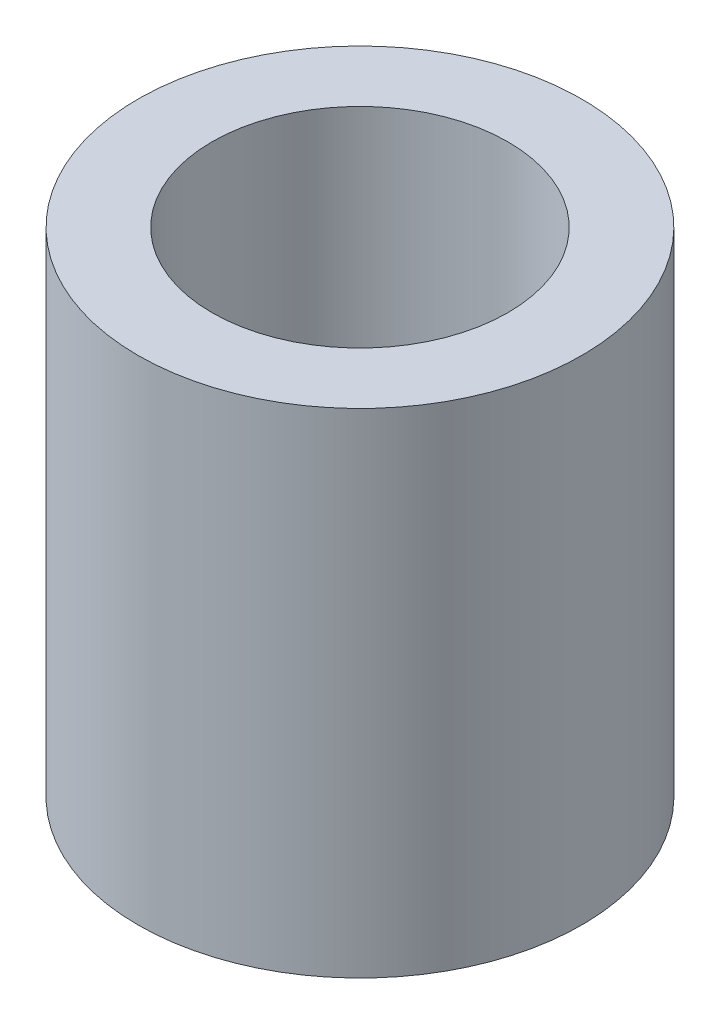
SolidWorks part; units mm, degrees
ref_plane "Front Plane" through (0, 0, 0) normal (0, 0, 1) x (1, 0, 0)
ref_plane "Top Plane" through (0, 0, 0) normal (0, 1, 0) x (1, 0, 0)
ref_plane "Right Plane" through (0, 0, 0) normal (1, 0, 0) x (0, 0, -1)
sketch "Sketch1" plane through (0, 0, 0) normal (0, 1, 0) x (1, 0, 0)
  circle A0 centre (0, 0) radius 1.5
  circle A1 centre (0, 0) radius 2.25
  dimension "D1" = 3
  dimension "D2" = 4.5
extrude "Boss-Extrude1" add sketch "Sketch1" along normal blind 5
